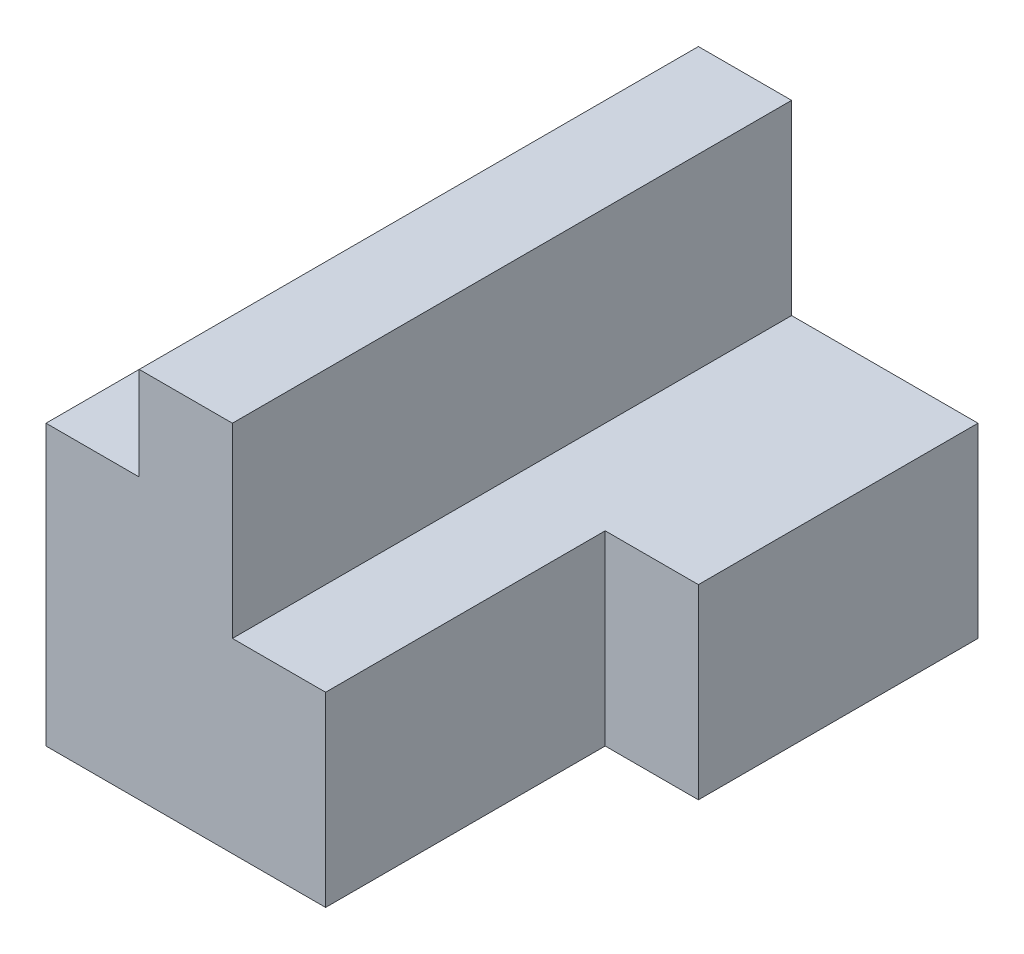
SolidWorks part; units mm, degrees
ref_plane "Front Plane" through (0, 0, 0) normal (0, 0, 1) x (1, 0, 0)
ref_plane "Top Plane" through (0, 0, 0) normal (0, 1, 0) x (1, 0, 0)
ref_plane "Right Plane" through (0, 0, 0) normal (1, 0, 0) x (0, 0, -1)
sketch "Sketch1" plane through (0, 0, 0) normal (0, 0, 1) x (1, 0, 0)
  line L1 (0, 0) -> (40, 0)
  line L2 (0, 0) -> (0, 40)
  line L3 (0, 40) -> (40, 40)
  line L4 (40, 0) -> (40, 40)
extrude "Boss-Extrude1" add sketch "Sketch1" along normal blind 60
sketch "Sketch2" plane through (0, 40, 0) normal (0, 1, 0) x (1, 0, 0)
  line L0 (40, 0) -> (0, 0) construction
  line L1 (40, -60) -> (20, -60)
  line L2 (40, -60) -> (40, 0)
  line L3 (40, 0) -> (20, 0)
  line L4 (20, -60) -> (20, 0)
extrude "Cut-Extrude1" cut sketch "Sketch2" against normal blind 20
sketch "Sketch3" plane through (0, 20, 0) normal (0, 1, 0) x (1, 0, 0)
  line L0 (40, -60) -> (40, 0) construction
  line L1 (30, -60) -> (40, -60)
  line L3 (30, -30) -> (40, -30)
  line L4 (40, -60) -> (40, -30)
  line L9 (30, -60) -> (30, -30)
extrude "Cut-Extrude2" cut sketch "Sketch3" against normal blind 20
sketch "Sketch4" plane through (0, 40, 0) normal (0, 1, 0) x (1, 0, 0)
  line L0 (20, 0) -> (0, 0) construction
  line L1 (0, -60) -> (10, -60)
  line L2 (0, -60) -> (0, 0)
  line L3 (0, 0) -> (10, 0)
  line L4 (10, -60) -> (10, 0)
extrude "Cut-Extrude3" cut sketch "Sketch4" against normal blind 10
